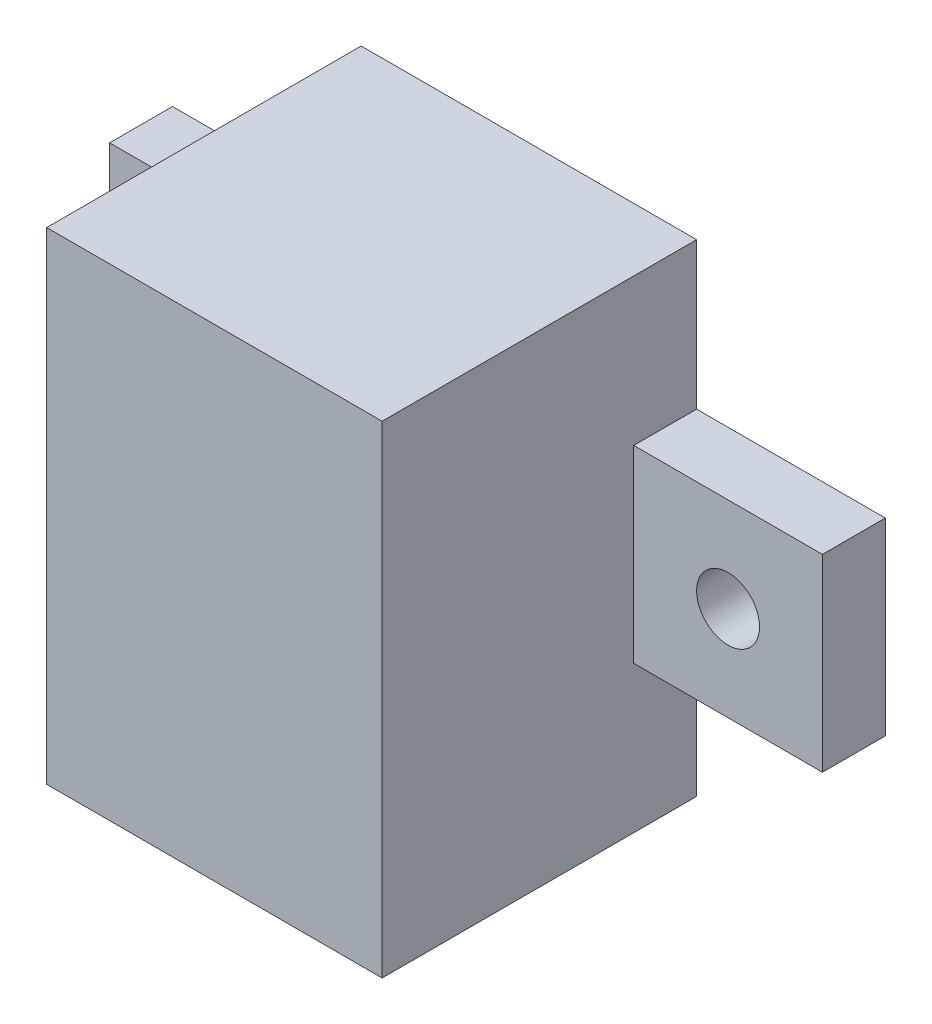
SolidWorks part; units mm, degrees
ref_plane "Front Plane" through (0, 0, 0) normal (0, 0, 1) x (1, 0, 0)
ref_plane "Top Plane" through (0, 0, 0) normal (0, 1, 0) x (1, 0, 0)
ref_plane "Right Plane" through (0, 0, 0) normal (1, 0, 0) x (0, 0, -1)
sketch "Sketch1" plane through (0, 0, 0) normal (0, 0, 1) x (1, 0, 0)
  line L0 (-12.5, 0) -> (12.5, 0) construction
  line L1 (8, 11.5) -> (-8, 11.5)
  line L2 (8, 11.5) -> (8, -11.5)
  line L3 (8, -11.5) -> (-8, -11.5)
  line L4 (-8, 11.5) -> (-8, -11.5)
  line L5 (8, 11.5) -> (-8, -11.5) construction
  line L6 (8, -11.5) -> (-8, 11.5) construction
  line L7 (-8, 4.5) -> (-17, 4.5)
  line L8 (-8, 4.5) -> (-8, -4.5)
  line L9 (-8, -4.5) -> (-17, -4.5)
  line L10 (-17, 4.5) -> (-17, -4.5)
  line L11 (8, 4.5) -> (17, 4.5)
  line L12 (8, 4.5) -> (8, -4.5)
  line L13 (8, -4.5) -> (17, -4.5)
  line L14 (17, 4.5) -> (17, -4.5)
  circle A0 centre (-12.5, 0) radius 1.5
  circle A1 centre (12.5, 0) radius 1.5
  point P0 (0, 0)
  point P18 (0, 0)
  point P20 (-17, 0)
  point P22 (-12.5, 4.5)
  dimension "D4" = 3
  dimension "D1" = 16
  dimension "D2" = 23
  dimension "D3" = 4.5
extrude "Boss-Extrude1" add sketch "Sketch1" along normal blind 15 contours L7 L10 L9 L4 A0 | L1 L4 L3 L2 | L14 L11 L2 L13 A1
sketch "Sketch2" plane through (0, -11.5, 0) normal (0, -1, 0) x (1, 0, 0)
  line L0 (8, 0) -> (-8, 0) construction
  line L1 (5, 2) -> (-5, 2)
  line L2 (5, 2) -> (5, 12)
  line L3 (5, 12) -> (-5, 12)
  line L4 (-5, 2) -> (-5, 12)
  line L5 (8, 15) -> (-8, 15) construction
  line L6 (-8, 15) -> (-8, 0) construction
  line L7 (17, 15) -> (17, 0) construction
  line L8 (4.25, 2) -> (-4.25, 2)
  line L9 (4.25, 2) -> (4.25, 0)
  line L10 (4.25, 0) -> (-4.25, 0)
  line L11 (-4.25, 2) -> (-4.25, 0)
  line L12 (17, 3) -> (8, 3)
  line L13 (17, 3) -> (17, 15)
  line L14 (17, 15) -> (8, 15)
  line L15 (8, 3) -> (8, 15)
  line L16 (-17, 15) -> (-17, 0) construction
  line L17 (-17, 3) -> (-8, 3)
  line L18 (-17, 3) -> (-17, 15)
  line L19 (-17, 15) -> (-8, 15)
  line L20 (-8, 3) -> (-8, 15)
  line L21 (8, 0) -> (17, 0) construction
  point P4 (0, 2)
  point P16 (0, 0)
  line M9 (-8, 0) -> (8, 0)
  line M10 (8, 0) -> (8, 15)
  line M12 (-8, 15) -> (-8, 0)
  dimension "D1" = 2
  dimension "D2" = 3
  dimension "D3" = 3
  dimension "D4" = 8.5
  dimension "D5" = 3
extrude "Cut-Extrude1" cut sketch "Sketch2" against normal blind 20 contours L4 L1 L2 L3 | L1 L11 L9 M9 | L13 L14 L12 M10 | L19 L18 L17 M12
